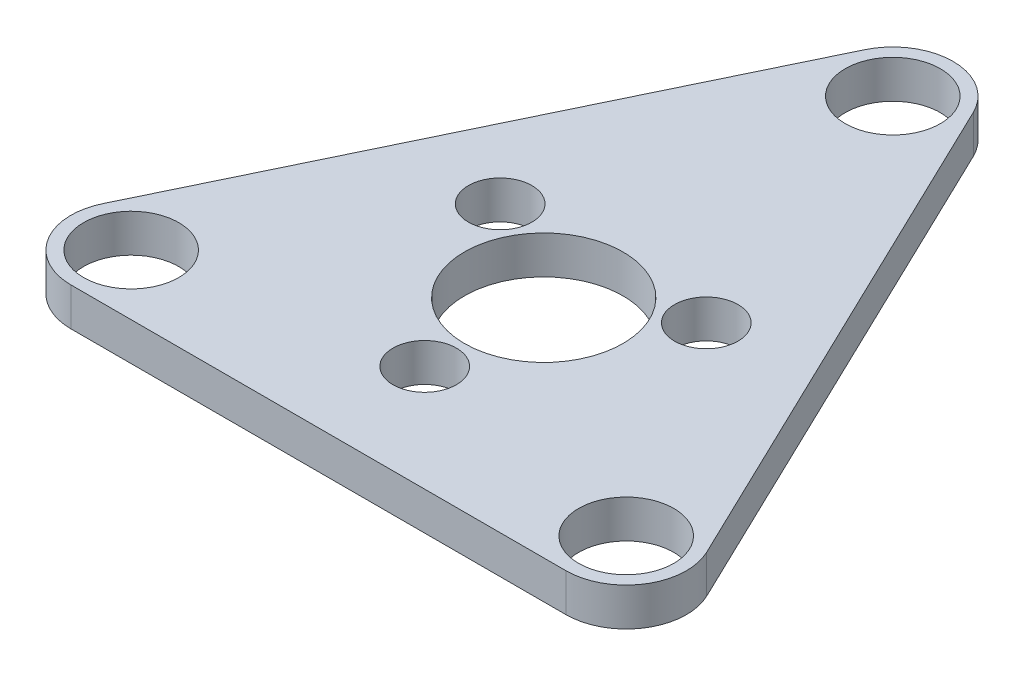
SolidWorks part; units mm, degrees
ref_plane "Front Plane" through (0, 0, 0) normal (0, 0, 1) x (1, 0, 0)
ref_plane "Top Plane" through (0, 0, 0) normal (0, 1, 0) x (1, 0, 0)
ref_plane "Right Plane" through (0, 0, 0) normal (1, 0, 0) x (0, 0, -1)
sketch "Sketch1" plane through (0, 0, 0) normal (0, 1, 0) x (1, 0, 0)
  line L0 (0, -55) -> (0, 55) construction
  line L1 (-95.119, -43.7575) -> (-17.119, 118.2425)
  line L2 (95.119, -43.7575) -> (17.119, 118.2425)
  line L3 (-78, -71) -> (78, -71)
  arc A0 (17.119, 118.2425) -> (-17.119, 118.2425) centre (0, 110) ccw
  arc A1 (-95.119, -43.7575) -> (-78, -71) centre (-78, -52) ccw
  arc A2 (95.119, -43.7575) -> (78, -71) centre (78, -52) cw
  circle A3 centre (0, 110) radius 15
  circle A4 centre (-78, -52) radius 15
  circle A5 centre (78, -52) radius 15
  circle A6 centre (0, 0) radius 25
  dimension "D1" = 38
  dimension "D5" = 30
  dimension "D6" = 50
  dimension "D2" = 78
  dimension "D3" = 52
  dimension "D4" = 162
extrude "Boss-Extrude1" add sketch "Sketch1" along normal mid plane 12
hole_wizard "Hole1" positions "Sketch2" profile "Sketch3" legacy end condition through all
sketch "Sketch2" plane through (0, 6, 0) normal (0, 1, 0) x (1, 0, 0)
  line L0 (0, 0) -> (25, 0) construction
  circle A0 centre (0, 0) radius 25 construction
  point P0 (0, -37.5)
  point P10 (0, 0)
  dimension "D1" = 37.5
sketch "Sketch3" plane through (0, 6, 37.5) normal (1, 0, 0) x (0, 0, 1)
  line L0 (0, 0) -> (0, 12)
  line L1 (0, 12) -> (10, 12)
  line L2 (10, 12) -> (10, 0)
  line L3 (10, 0) -> (0, 0)
  line L4 (0, 110) -> (0, -10) construction
  dimension "Diameter" = 20
  dimension "Depth" = 12
pattern_circular "CirPattern1" count 3 over 360 about axis through (0, 0, 0) along (0, 1, 0) of "Hole1"
